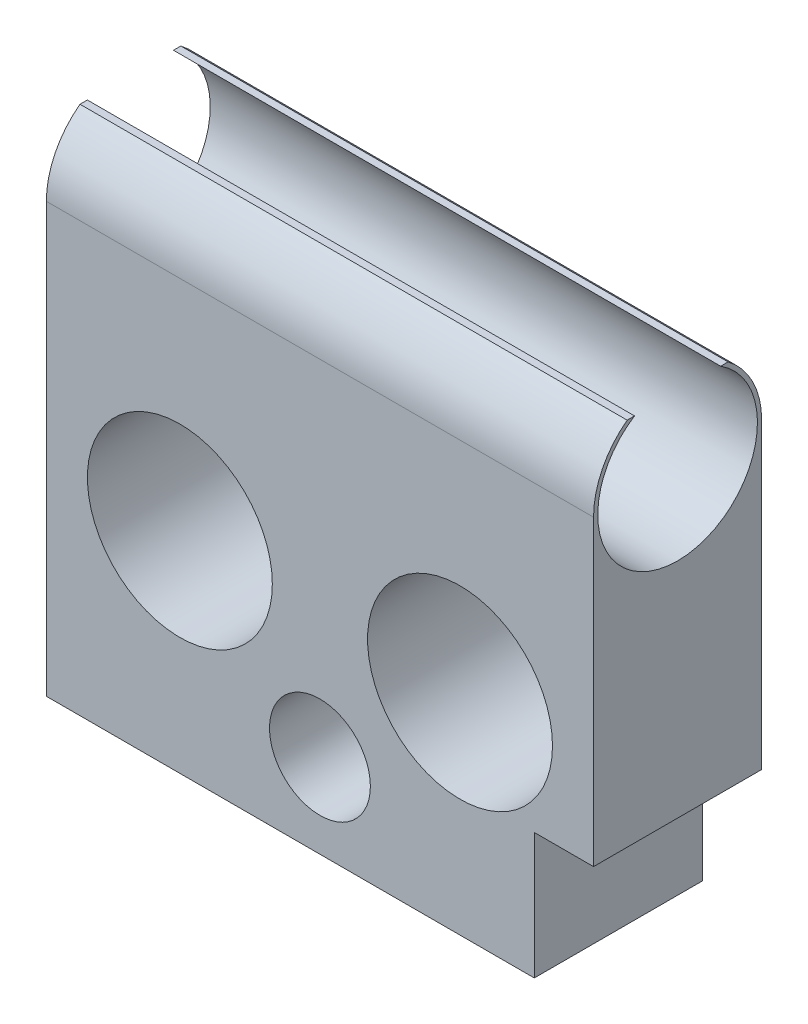
SolidWorks part; units mm, degrees
material "Manual Density from Real Component Plastica Fusoliera"
ref_plane "Piano frontale" through (0, 0, 0) normal (0, 0, 1) x (1, 0, 0)
ref_plane "Piano superiore" through (0, 0, 0) normal (0, 1, 0) x (1, 0, 0)
ref_plane "Piano destro" through (0, 0, 0) normal (1, 0, 0) x (0, 0, -1)
sketch "Schizzo1" plane through (0, 0, 0) normal (0, 0, 1) x (1, 0, 0)
  line L0 (-15.55, 0) -> (15.55, 0) construction
  line L2 (-30.55, 15) -> (30.55, 15) construction
  line L3 (-30.55, 15) -> (-30.55, -25) construction
  line L4 (-30.55, -25) -> (30.55, -25)
  line L5 (30.55, 15) -> (30.55, -25) construction
  line L6 (-30.55, -15) -> (30.55, -15) construction
  line L7 (-30.55, -25) -> (-32.55, -25)
  line L8 (-32.55, -25) -> (-32.55, 17)
  line L9 (-32.55, 17) -> (32.55, 17) construction
  line L10 (32.55, 17) -> (32.55, -25)
  line L11 (32.55, -25) -> (30.55, -25)
  line L13 (-32.55, 17) -> (32.55, 17) construction
  line L14 (-32.55, 17) -> (-32.55, 37)
  line L15 (-32.55, 37) -> (32.55, 37)
  line L16 (32.55, 17) -> (32.55, 37)
  circle A0 centre (-15.55, 0) radius 15 construction
  circle A1 centre (15.55, 0) radius 15 construction
  point P5 (0, 0)
  dimension "D2" = 30
  dimension "D1" = 31.1
  dimension "D3" = 10
  dimension "D4" = 2
  dimension "D5" = 2
  dimension "D6" = 2
  dimension "D7" = 20
extrude "ParallelepipedoBlocco" add sketch "Schizzo1" along normal blind 20
sketch "Schizzo2" plane through (0, 0, 20) normal (0, 0, 1) x (1, 0, 0)
  line L0 (-16.665, 0) -> (16.665, 0) construction
  line L3 (-32.55, 15) -> (32.55, 15) construction
  line L4 (-32.55, 37) -> (-32.55, -25) construction
  line L5 (32.55, -25) -> (32.55, 37) construction
  line L7 (-30.55, 17) -> (-30.55, -25) construction
  line L8 (-32.55, -25) -> (32.55, -25) construction
  line L9 (32.55, 17) -> (-32.55, 17) construction
  line L10 (32.55, -25) -> (32.55, 37) construction
  line L11 (-32.55, 37) -> (-32.55, -25) construction
  circle A0 centre (-16.665, 0) radius 11
  circle A1 centre (16.665, 0) radius 11
  circle A2 centre (0, -15) radius 6
  point P4 (0, 0)
  dimension "D5" = 22
  dimension "D6" = 12
  dimension "D1" = 2
  dimension "D2" = 2
  dimension "D3" = 20
  dimension "D4" = 33.33
  dimension "D7" = 15
extrude "ForiTubiMotori" cut sketch "Schizzo2" against normal through all
sketch "Schizzo4" plane through (-32.55, 0, 0) normal (-1, 0, 0) x (0, 0, 1)
  line L0 (20, 37) -> (0, 37) construction
  circle A0 centre (10, 26) radius 9.5
  point P6 (10, 37)
  dimension "D1" = 19
  dimension "D2" = 11
extrude "ForoLongherone" cut sketch "Schizzo4" against normal through all
sketch "Schizzo5" plane through (-32.55, 0, 0) normal (-1, 0, 0) x (0, 0, 1)
  line L0 (20, 37) -> (20, -25) construction
  line L1 (0, 26) -> (0, 37)
  line L2 (0, -34.1) -> (0, 34.1) construction
  line L3 (0, 37) -> (20, 37)
  line L4 (20, 37) -> (20, 26)
  arc A0 (20, 26) -> (0, 26) centre (10, 26) ccw
extrude "EliminazioneParteSuperiore" cut sketch "Schizzo5" against normal through all
ref_plane "PianoMezzeriaLongherone" through (0, 0, 10) normal (0, 0, 1) x (1, 0, 0)
sketch "Schizzo6" plane through (0, 0, 20) normal (0, 0, 1) x (1, 0, 0)
  line L1 (32.55, -25) -> (25.5, -25)
  line L2 (32.55, -25) -> (32.55, -10)
  line L3 (32.55, -10) -> (25.5, -10)
  line L4 (25.5, -25) -> (25.5, -10)
  dimension "D1" = 15
  dimension "D2" = 7.05
extrude "SpazioMovimentoLevetta" cut sketch "Schizzo6" against normal through all
sketch "Schizzo7" plane through (-32.55, 0, 0) normal (-1, 0, 0) x (0, 0, 1)
  line L0 (0, -33.55) -> (0, 33.55) construction
  line L1 (0, 36) -> (20, 36)
  line L2 (0, 36) -> (0, 34)
  line L3 (0, 34) -> (20, 34)
  line L4 (20, 36) -> (20, 34)
  line L5 (20, 26) -> (20, -25) construction
  arc A0 (20, 26) -> (0, 26) centre (10, 26) ccw construction
  dimension "D1" = 2
extrude "TaglioPorzioneSuperiore" cut sketch "Schizzo7" against normal up to surface (65.1 mm away) up to face at (32.55, 26, 19.5)
